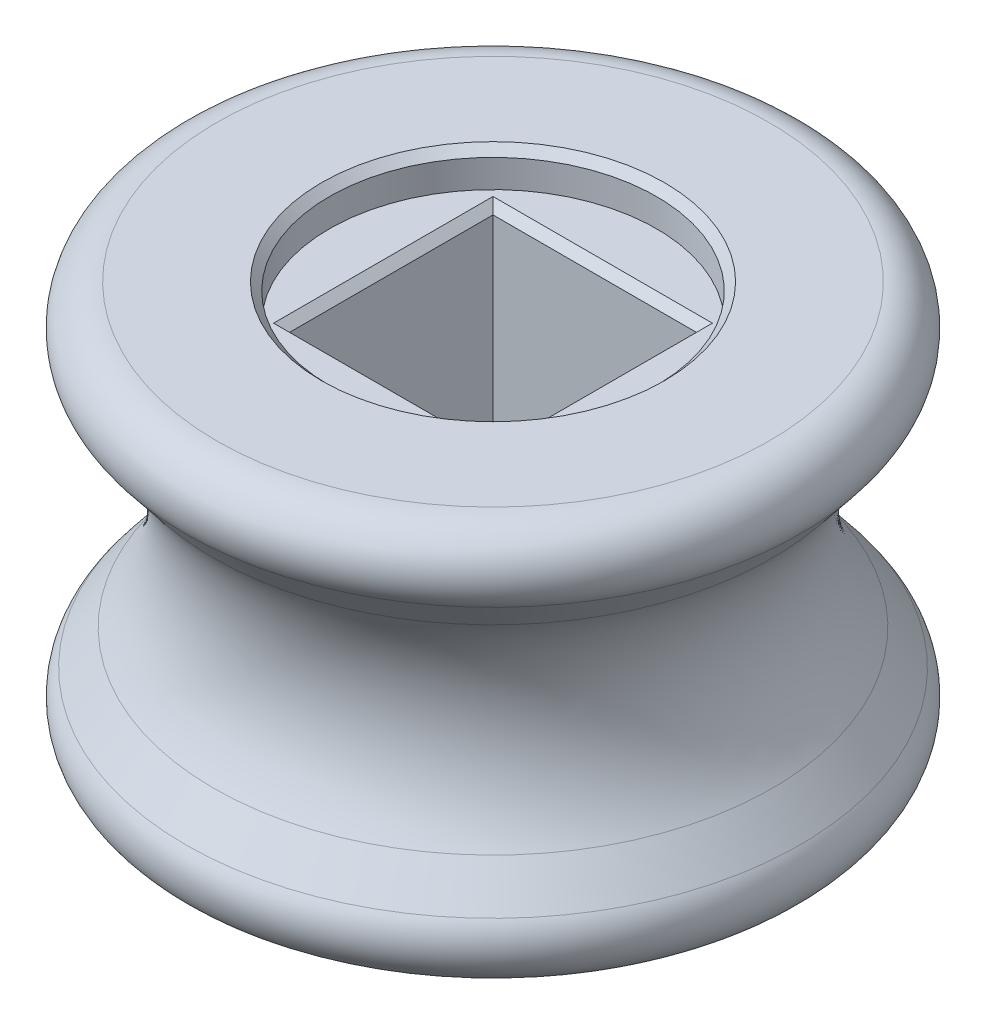
SolidWorks part; units mm, degrees
ref_plane "Front Plane" through (0, 0, 0) normal (0, 0, 1) x (1, 0, 0)
ref_plane "Top Plane" through (0, 0, 0) normal (0, 1, 0) x (1, 0, 0)
ref_plane "Right Plane" through (0, 0, 0) normal (1, 0, 0) x (0, 0, -1)
sketch "Sketch1" plane through (0, 0, 0) normal (0, 0, 1) x (1, 0, 0)
  line L0 (0, 0) -> (0, 12.7) construction
  line L1 (4.7625, 0) -> (4.7625, 3.302)
  line L2 (4.7625, 3.302) -> (2.8575, 3.302)
  line L3 (2.8575, 3.302) -> (2.8575, 9.398)
  line L4 (2.8575, 9.398) -> (4.7625, 9.398)
  line L5 (4.7625, 9.398) -> (4.7625, 12.7)
  line L6 (4.7625, 12.7) -> (11.43, 12.7)
  line L7 (11.43, 12.7) -> (6.35, 6.35)
  line L8 (6.35, 6.35) -> (11.43, 0)
  line L9 (11.43, 0) -> (4.7625, 0)
  point P13 (0, 6.35)
  dimension "D1" = 12.7
  dimension "D2" = 3.302
  dimension "D3" = 9.525
  dimension "D4" = 5.715
  dimension "D5" = 5.08
  dimension "D6" = 11.43
revolve "Revolve1" add sketch "Sketch1" angle 360 about L0
fillet "Fillet1" radius 5.08 1 edges at (0, 6.35, -6.35)
fillet "Fillet2" radius 1.27 2 edges at (0, 0, -11.43) (0, 12.7, -11.43)
chamfer "Chamfer1" [suppressed] distance 0.635 angle 45
sketch "Sketch2" plane through (0, 9.398, 0) normal (0, 1, 0) x (1, 0, 0)
  line L1 (-3.2385, -3.2385) -> (3.2385, -3.2385)
  line L2 (-3.2385, -3.2385) -> (-3.2385, 3.2385)
  line L3 (-3.2385, 3.2385) -> (3.2385, 3.2385)
  line L4 (3.2385, -3.2385) -> (3.2385, 3.2385)
  line L5 (-3.2385, -3.2385) -> (3.2385, 3.2385) construction
  line L6 (-3.2385, 3.2385) -> (3.2385, -3.2385) construction
  circle A0 centre (0, 0) radius 4.7625
  point P0 (0, 0)
  dimension "D1" = 6.477
extrude "Boss-Extrude1" add sketch "Sketch2" along normal up to surface and the other way up to surface up to face at (0, 12.7, 8.7876) other way up to face at (0, 0, -8.7876)
sketch "Sketch3" plane through (0, 9.398, 0) normal (0, 1, 0) x (1, 0, 0)
  line L1 (3.2385, -3.2385) -> (-3.2385, -3.2385)
  line L2 (3.2385, -3.2385) -> (3.2385, 3.2385)
  line L3 (3.2385, 3.2385) -> (-3.2385, 3.2385)
  line L4 (-3.2385, -3.2385) -> (-3.2385, 3.2385)
  line L5 (3.2385, -3.2385) -> (-3.2385, 3.2385) construction
  line L6 (3.2385, 3.2385) -> (-3.2385, -3.2385) construction
  point P0 (0, 0)
extrude "Cut-Extrude1" cut sketch "Sketch3" against normal through all
sketch "Sketch4" plane through (0, 12.7, 0) normal (0, 1, 0) x (1, 0, 0)
  circle A0 centre (0, 0) radius 5.207
  dimension "D1" = 10.414
extrude "Cut-Extrude2" cut sketch "Sketch4" against normal blind 1.143
ref_plane "Plane1" through (0, 6.35, 0) normal (0, 1, 0) x (1, 0, 0)
mirror "Mirror1" about plane through (0, 6.35, 0) normal (0, 1, 0) of "Cut-Extrude2"
chamfer "Chamfer2" distance 0.254 angle 45 10 edges at (0, 12.7, 5.207) (0, 1.143, 3.2385) (-3.2385, 1.143, 0) (0, 1.143, -3.2385) (3.2385, 1.143, 0) (0, 11.557, 3.2385) (3.2385, 11.557, 0) (0, 11.557, -3.2385) (-3.2385, 11.557, 0) (0, 0, 5.207)
